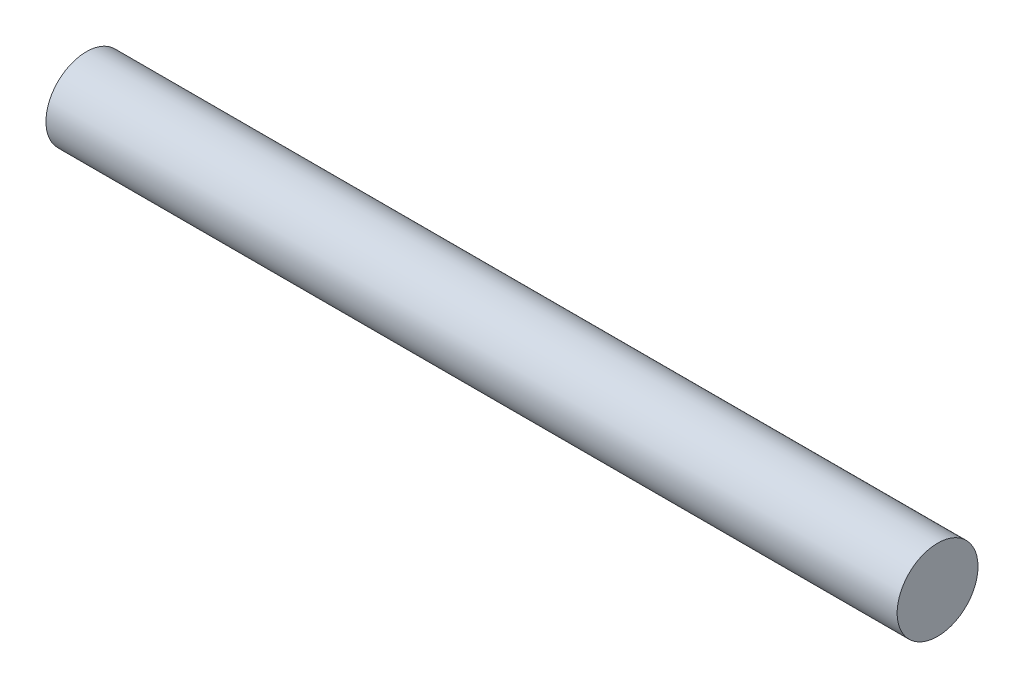
SolidWorks part; units mm, degrees
ref_plane "Plano frontal" through (0, 0, 0) normal (0, 0, 1) x (1, 0, 0)
ref_plane "Plano superior" through (0, 0, 0) normal (0, 1, 0) x (1, 0, 0)
ref_plane "Plano direito" through (0, 0, 0) normal (1, 0, 0) x (0, 0, -1)
sketch "Esboço1" plane through (0, 0, 0) normal (1, 0, 0) x (0, 0, -1)
  circle A0 centre (0, 0) radius 25.4
  dimension "D1" = 50.8
extrude "Ressalto-extrusão1" add sketch "Esboço1" along normal mid plane 535
